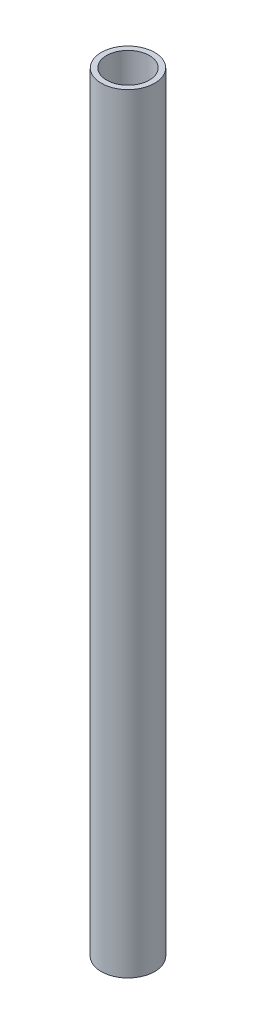
SolidWorks part; units mm, degrees
ref_plane "Front Plane" through (0, 0, 0) normal (0, 0, 1) x (1, 0, 0)
ref_plane "Top Plane" through (0, 0, 0) normal (0, 1, 0) x (1, 0, 0)
ref_plane "Right Plane" through (0, 0, 0) normal (1, 0, 0) x (0, 0, -1)
sketch "Sketch2" plane through (0, 0, 0) normal (0, 1, 0) x (1, 0, 0)
  circle A0 centre (0, 0) radius 15
  circle A1 centre (0, 0) radius 12
  dimension "D1" = 30
  dimension "D2" = 24
extrude "Boss-Extrude1" add sketch "Sketch2" along normal blind 432
